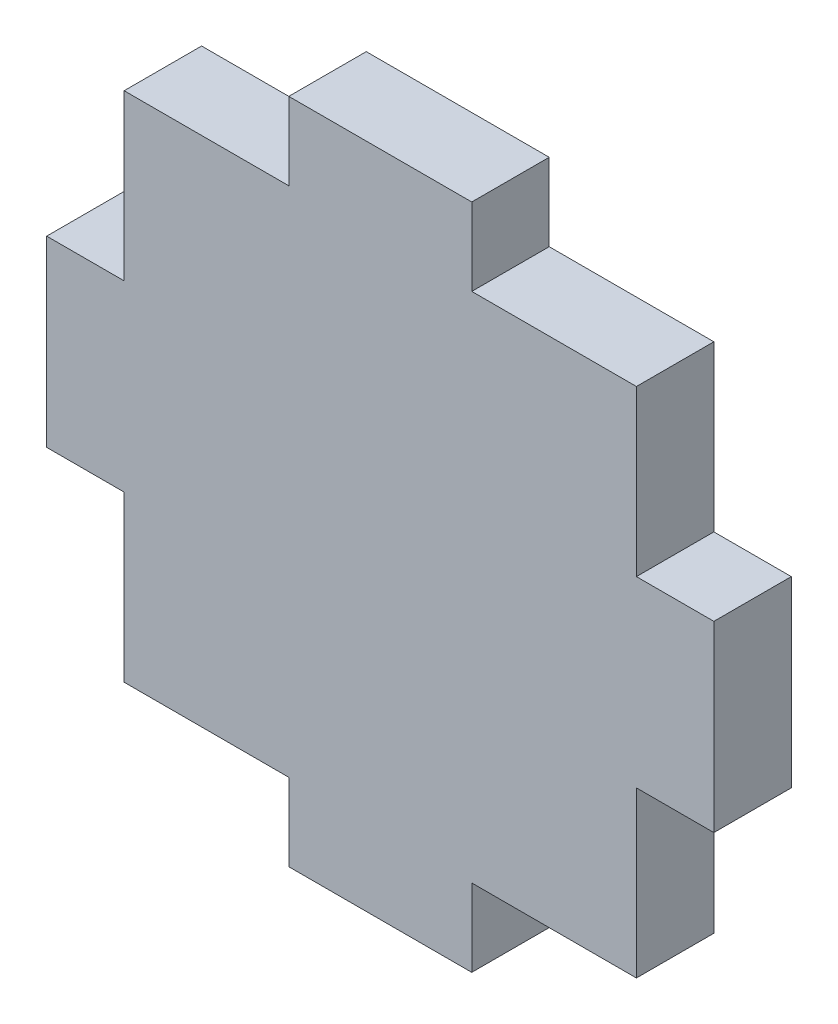
SolidWorks part; units mm, degrees
ref_plane "Front Plane" through (0, 0, 0) normal (0, 0, 1) x (1, 0, 0)
ref_plane "Top Plane" through (0, 0, 0) normal (0, 1, 0) x (1, 0, 0)
ref_plane "Right Plane" through (0, 0, 0) normal (1, 0, 0) x (0, 0, -1)
sketch "Sketch1" plane through (0, 0, 0) normal (0, 0, 1) x (1, 0, 0)
  line L1 (27.35, -27.35) -> (-27.35, -27.35)
  line L2 (27.35, -27.35) -> (27.35, 27.35)
  line L3 (27.35, 27.35) -> (-27.35, 27.35)
  line L4 (-27.35, -27.35) -> (-27.35, 27.35)
  line L5 (27.35, -27.35) -> (-27.35, 27.35) construction
  line L6 (27.35, 27.35) -> (-27.35, -27.35) construction
  point P0 (0, 0)
  dimension "D1" = 54.7
extrude "Boss-Extrude1" add sketch "Sketch1" along normal blind 6.35
sketch "Sketch2" plane through (0, 0, 6.35) normal (0, 0, 1) x (1, 0, 0)
  line L0 (27.35, 27.35) -> (-27.35, 27.35) construction
  line L1 (-27.35, 27.35) -> (-7.5, 27.35)
  line L2 (-27.35, 27.35) -> (-27.35, 21)
  line L3 (-27.35, 21) -> (-7.5, 21)
  line L4 (-7.5, 27.35) -> (-7.5, 21)
  line L5 (-27.35, 27.35) -> (-27.35, -27.35) construction
  line L7 (27.35, 27.35) -> (7.5, 27.35)
  line L8 (27.35, 27.35) -> (27.35, 21)
  line L9 (27.35, 21) -> (7.5, 21)
  line L10 (7.5, 27.35) -> (7.5, 21)
  line L11 (-27.35, 27.35) -> (-21, 27.35)
  line L12 (-27.35, 27.35) -> (-27.35, 7.5)
  line L13 (-27.35, 7.5) -> (-21, 7.5)
  line L14 (-21, 27.35) -> (-21, 7.5)
  line L15 (-27.35, -27.35) -> (-21, -27.35)
  line L16 (-27.35, -27.35) -> (-27.35, -7.5)
  line L17 (-27.35, -7.5) -> (-21, -7.5)
  line L18 (-21, -27.35) -> (-21, -7.5)
  line L19 (27.35, -27.35) -> (21, -27.35)
  line L20 (27.35, -27.35) -> (27.35, -7.5)
  line L21 (27.35, -7.5) -> (21, -7.5)
  line L22 (21, -27.35) -> (21, -7.5)
  line L23 (27.35, -27.35) -> (7.5, -27.35)
  line L24 (27.35, -27.35) -> (27.35, -21)
  line L25 (27.35, -21) -> (7.5, -21)
  line L26 (7.5, -27.35) -> (7.5, -21)
  line L27 (27.35, 27.35) -> (21, 27.35)
  line L28 (27.35, 27.35) -> (27.35, 7.5)
  line L29 (27.35, 7.5) -> (21, 7.5)
  line L30 (21, 27.35) -> (21, 7.5)
  line L31 (-27.35, -27.35) -> (-7.5, -27.35)
  line L32 (-27.35, -27.35) -> (-27.35, -21)
  line L33 (-27.35, -21) -> (-7.5, -21)
  line L34 (-7.5, -27.35) -> (-7.5, -21)
  point P37 (-7.5, -17.825)
  line M5 (-27.35, 27.35) -> (-27.35, -27.35)
  line M6 (-27.35, -27.35) -> (27.35, -27.35)
  line M7 (27.35, -27.35) -> (27.35, 27.35)
  line M8 (27.35, 27.35) -> (-27.35, 27.35)
  dimension "D1" = 6.35
  dimension "D2" = 15
extrude "Cut-Extrude1" cut sketch "Sketch2" against normal through all contours L14 L3 L13 M5 | L14 L1 L3 M5 | L14 L3 L4 M8 | L30 L7 L10 L9 | L30 L9 M8 M7 | L9 L30 L29 M7 | L25 L20 L21 L22 | L25 L22 M7 M6 | L26 L22 L25 M6 | L34 L33 L18 M6 | L33 L16 L18 M6 | L33 L18 L17 M5
